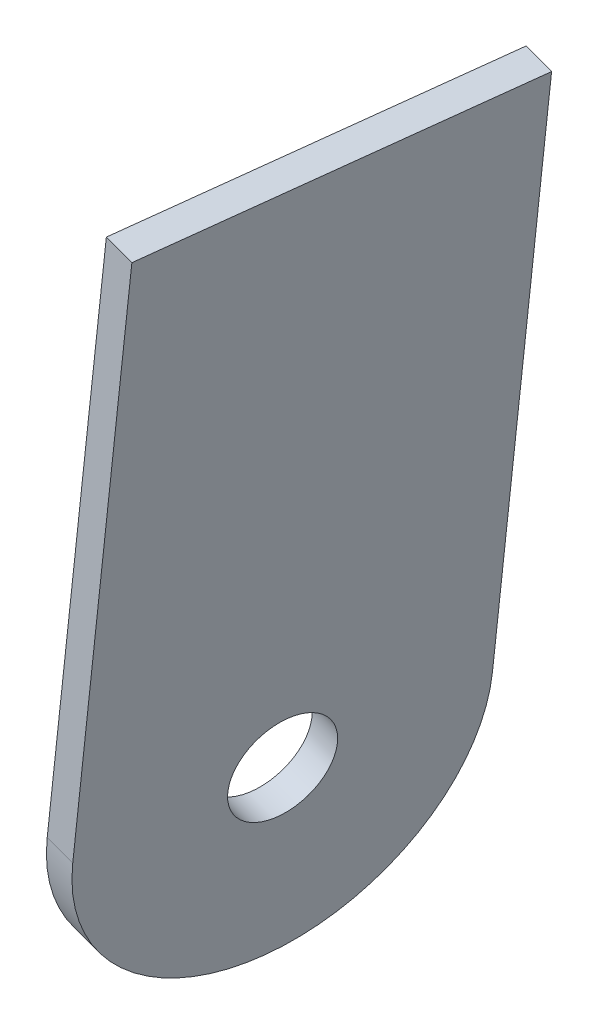
SolidWorks part; units mm, degrees
ref_plane "Front Plane" through (0, 0, 0) normal (0, 0, 1) x (1, 0, 0)
ref_plane "Top Plane" through (0, 0, 0) normal (0, 1, 0) x (1, 0, 0)
ref_plane "Right Plane" through (0, 0, 0) normal (1, 0, 0) x (0, 0, -1)
ref_plane "Plane1" through (-406.4343, 66.9882, -60.0804) normal (-0.9764, 0.1609, -0.1443) x (-0.1424, 0.0235, 0.9895)
sketch "Sketch2" plane through (-406.4343, 66.9882, -60.0804) normal (-0.9764, 0.1609, -0.1443) x (-0.1424, 0.0235, 0.9895)
  line L0 (-544.7858, 305.6554) -> (-546.4574, 275.2213)
  line L1 (-74.0304, 279.7982) -> (-708.5122, 314.6484) construction
  line L2 (-527.4361, 274.1765) -> (-525.7645, 304.6106)
  line L3 (-525.7645, 304.6106) -> (-544.7858, 305.6554)
  line L4 (-536.7928, 277.5014) -> (-537.1007, 271.8964) construction
  arc A0 (-546.4574, 275.2213) -> (-527.4361, 274.1765) centre (-536.9468, 274.6989) ccw
  circle A1 centre (-536.9468, 274.6989) radius 2.4892
  dimension "D1" = 9.525
  dimension "D2" = 4.9784
extrude "Boss-Extrude1" add sketch "Sketch2" along normal blind 1.5875
